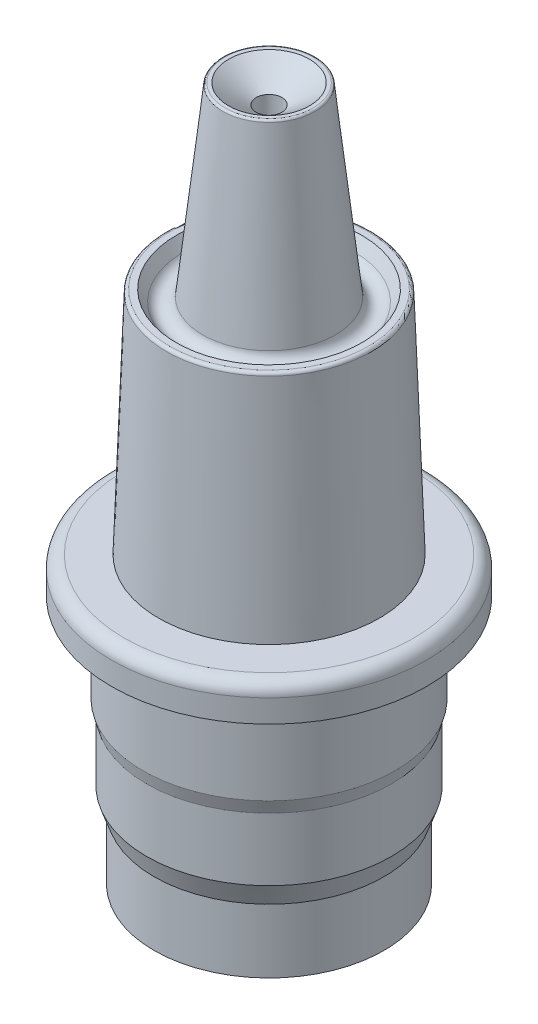
SolidWorks part; units mm, degrees
material "PE Baixa/Média Densidade"
ref_plane "Frontal" through (0, 0, 0) normal (0, 0, 1) x (1, 0, 0)
ref_plane "Superior" through (0, 0, 0) normal (0, 1, 0) x (1, 0, 0)
ref_plane "Lateral" through (0, 0, 0) normal (1, 0, 0) x (0, 0, -1)
sketch "Sketch1" plane through (0, 0, 0) normal (0, 0, 1) x (1, 0, 0)
  line L0 (0, -0.8) -> (0, 33.7609) construction
  line L1 (4.5, 0) -> (5.4, 0)
  line L2 (4.5, 0) -> (4.0613, 22.5092)
  line L3 (5.4, 0) -> (5.4, 3)
  line L4 (5.4, 3) -> (5.75, 4)
  line L5 (7.4, 11.74) -> (7.4, 13.41)
  line L6 (7.4, 13.41) -> (5.185, 13.41)
  line L8 (2.16, 32.61) -> (1.9, 32.61)
  line L9 (0.4391, 28.25) -> (0, 28.25)
  line L10 (1.9, 32.61) -> (0.6016, 31.7009)
  line L11 (0.5391, 28.3481) -> (0.6016, 31.7009)
  line L12 (2.16, 32.61) -> (3.115, 23.9018)
  line L13 (5.75, 4) -> (5.75, 6.95)
  line L14 (1.25, 30.99) -> (1.0582, 25.4973)
  line L15 (5.75, 6.95) -> (5.915, 7.57)
  line L16 (2.4032, 23.9928) -> (1.6359, 30.99)
  line L17 (4.365, 24.21) -> (4.0343, 23.6885)
  line L18 (1.0582, 25.4973) -> (0.735, 25.4973)
  line L19 (2.16, 32.61) -> (2.16, 35.9772) construction
  line L20 (5.915, 7.57) -> (5.915, 11.74)
  line L21 (-4.1686, 23.41) -> (9.5782, 23.41) construction
  line L22 (0.735, 27.85) -> (0.735, 25.4973)
  line L23 (0, 28.25) -> (0, 27.95)
  line L24 (-1.9, 32.61) -> (-0.6016, 31.7009) construction
  line L25 (3.8943, 22.6563) -> (3.9113, 22.6563)
  line L26 (4.8129, 24.0652) -> (5.185, 13.41)
  line L27 (4.365, 24.21) -> (4.663, 24.21)
  line L28 (1.6359, 30.99) -> (1.25, 30.99)
  line L29 (5.915, 11.74) -> (7.4, 11.74)
  line L30 (0.635, 27.95) -> (0, 27.95)
  arc A0 (3.115, 23.9018) -> (4.0343, 23.6885) centre (3.612, 23.9563) ccw
  arc A1 (3.9113, 22.6563) -> (4.0613, 22.5092) centre (3.9113, 22.5063) cw
  arc A2 (4.8129, 24.0652) -> (4.663, 24.21) centre (4.663, 24.06) ccw
  arc A3 (0.4391, 28.25) -> (0.5391, 28.3481) centre (0.4391, 28.35) ccw
  arc A4 (0.735, 27.85) -> (0.635, 27.95) centre (0.635, 27.85) ccw
  arc A7 (2.4032, 23.9928) -> (3.8943, 22.6563) centre (3.8943, 24.1563) ccw
  point P18 (0, 32.3938)
  point P22 (5.7667, 23.41)
  point P24 (0.5287, 31.6388)
  point P25 (1.8499, 28.06)
  point P30 (0, 31.4721)
  point P38 (4.8079, 24.21)
  dimension "D9" = 0.6976
  dimension "D11" = 10.8
  dimension "D12" = 5.4927
  dimension "D13" = 19.2
  dimension "D14" = 6.258
  dimension "D21" = 8.4
  dimension "D32" = 2.5
  dimension "D10" = 1.2032
  dimension "D27" = 30.99
  dimension "D19" = 8.73
  dimension "D37" = 2
  dimension "D6" = 14.8
  dimension "D17" = 0.5
  dimension "D5" = 0.3859
  dimension "D44" = 0.7537
  dimension "D46" = 3.2718
  dimension "D20" = 3.8
  dimension "D22" = 9.6258
  dimension "D29" = 1.62
  dimension "D33" = 2.1164
  dimension "D35" = 1.5
  dimension "D42" = 22.6563
  dimension "D43" = 1
  dimension "D45" = 6.23
  dimension "D34" = 0.15
  dimension "D49" = 110
  dimension "D50" = 2.95
  dimension "D31" = 4.36
  dimension "D38" = 0.1
  dimension "D16" = 1.069
  dimension "D52" = 0.62
  dimension "D36" = 0.1
  dimension "D4" = 1.117
  dimension "D7" = 9.2
  dimension "D8" = 4.32
  dimension "D15" = 1.67
  dimension "D18" = 0.8
  dimension "D23" = 3
  dimension "D24" = 0.3
  dimension "D25" = 55
  dimension "D26" = 0.9
  dimension "D28" = 11.5
  dimension "D30" = 11.83
  dimension "D39" = 10.37
  dimension "D41" = 2
  dimension "D47" = 5.4927
  dimension "D48" = 4.8065
  dimension "D51" = 0.9091
  dimension "D53" = 4.17
  dimension "D54" = 0.3232
revolve "Base-Revolve" add sketch "Sketch1" angle 360 about L0
fillet "Fillet3" radius 0.6 1 edges at (0, 13.41, -7.4)
sketch "Esboço1" plane through (0, 0, 0) normal (1, 0, 0) x (0, 0, -1)
  line L0 (-1.6359, 30.99) -> (-2.4032, 23.9928) construction
  line L1 (-1.6359, 30.99) -> (-1, 30.99)
  line L2 (-1.6359, 30.99) -> (1.6359, 30.99) construction
  line L3 (1, 30.99) -> (0.8082, 25.4973)
  line L4 (2.2382, 25.4973) -> (0.8082, 25.4973)
  line L5 (1.6359, 30.99) -> (2.2382, 25.4973)
  line L6 (1.6359, 30.99) -> (1, 30.99)
  line L7 (-1.6359, 30.99) -> (-2.4032, 23.9928) construction
  line L8 (0, 32.8607) -> (0, 22.4082) construction
  line L9 (-1.0582, 25.4973) -> (1.0582, 25.4973) construction
  line L10 (-1.25, 30.99) -> (-1.0582, 25.4973) construction
  line L11 (-1.6359, 30.99) -> (-2.2382, 25.4973)
  line L13 (-2.2382, 25.4973) -> (-0.8082, 25.4973)
  line L15 (-1, 30.99) -> (-0.8082, 25.4973)
  dimension "D1" = 2
extrude "Extrusão1" add sketch "Esboço1" along normal mid plane 0.6
fillet "Filete1" radius 0.2 2 edges at (1.6359, 30.99, 0) (-1.6359, 30.99, 0)
pattern_circular "PadrãoCircular1" count 4 over 360 about axis through (0, 22.5092, 0) along (0, -1, 0) of "Extrusão1"
ref_plane "Plano1" through (0, 0, 0) normal (0.7071, 0, 0.7071) x (0.7071, 0, -0.7071)
fillet "Filete2" radius 0.1 1 edges at (0, 32.61, -2.16)
scale "Molde 2%" [suppressed]
sketch "Esboço3" plane through (0, 0, 0) normal (0, 0, 1) x (1, 0, 0)
  spline S0 degree 3 poles (6.8105, 32.0839) (1.93, 36.2002) (-4.826, 36.4314) (-7.1188, 30.8074) (-8.7117, 26.2562) (-6.6489, 20.9155) (-2.122, 22.1856) (-0.7831, 19.0617) (1.9916, 19.563) (3.2081, 16.9542) (6.7382, 15.821) (9.2078, 20.6481) (8.1743, 25.5707) (6.8105, 32.0839) (1.93, 36.2002) (-4.826, 36.4314) knots -0.344116 -0.226043 -0.137397 0 0.079728 0.174637 0.279644 0.343324 0.424887 0.456243 0.496478 0.54283 0.592016 0.655884 0.773957 0.862603 1 1.079728 1.174637 1.279644 only from (0.5148, 35.8705) to (0.5148, 35.8705)
sketch "Esboço4" plane through (0, 0, 0) normal (0, 0, 1) x (1, 0, 0)
  line L0 (0, 33.3658) -> (0, 16.6091) construction
  line L1 (-2.1698, 32.5209) -> (-3.115, 23.9018) construction
  line L2 (-1.0582, 25.4973) -> (1.0582, 25.4973) construction
  line L4 (-1.245, 30.99) -> (-1.06, 25.4973)
  line L5 (-1.245, 30.99) -> (-2.1698, 32.5209)
  line L6 (-1.06, 25.4973) -> (-1.7393, 25.4973)
  line L9 (-1.4566, 30.99) -> (1.4566, 30.99) construction
  line L10 (4.365, 24.21) -> (-4.365, 24.21) construction
  line L12 (-4.8129, 24.0652) -> (-5.0872, 16.21)
  line L13 (-2.2393, 24.9973) -> (-2.2393, 16.21)
  line L14 (-2.1698, 32.5209) -> (-3.0812, 24.21)
  line L15 (-3.0812, 24.21) -> (-4.663, 24.21)
  line L17 (-4.8129, 24.0652) -> (-5.185, 13.41) construction
  line L19 (-2.2393, 16.21) -> (-5.0872, 16.21)
  arc A0 (-4.663, 24.21) -> (-4.8129, 24.0652) centre (-4.663, 24.06) ccw construction
  arc A3 (-2.2393, 24.9973) -> (-1.7393, 25.4973) centre (-1.7393, 24.9973) cw
  arc A7 (-4.663, 24.21) -> (-4.8129, 24.0652) centre (-4.663, 24.06) ccw
  dimension "D2" = 0.5
  dimension "D3" = 2.12
  dimension "D1" = 8
  dimension "D4" = 1.929
  dimension "D5" = 4.4785
revolve "Para vendedores 2" [suppressed] add sketch "Esboço4" angle 360 about L0
extrude "Para vendedores" [suppressed] cut sketch "Esboço3" along normal blind 10
sketch "Esboço5" plane through (0, 0, 0) normal (1, 0, 0) x (0, 0, -1)
  line L0 (-2.4848, 23.6433) -> (-4.1271, 19.131)
  line L1 (-4.0613, 22.5092) -> (-4.5, 0) construction
  line L2 (-4.0613, 22.5092) -> (-4.1271, 19.131)
  line L3 (0, 21.5298) -> (0, 16.2429) construction
  arc A0 (-3.8943, 22.6563) -> (-2.4032, 23.9928) centre (-3.8943, 24.1563) ccw construction
  arc A2 (-3.8943, 22.6563) -> (-2.4848, 23.6433) centre (-3.8943, 24.1563) ccw
  arc A3 (-3.8943, 22.6563) -> (-4.0613, 22.5092) centre (-3.9104, 22.5063) ccw
  dimension "D1" = 20
  dimension "D2" = 3.5253
extrude "Ressalto-extrusão1" add sketch "Esboço5" along normal mid plane 0.6
pattern_circular "PadrãoCircular2" count 8 over 360 about axis through (0, 0, 0) along (0, 1, 0) of "Ressalto-extrusão1"
